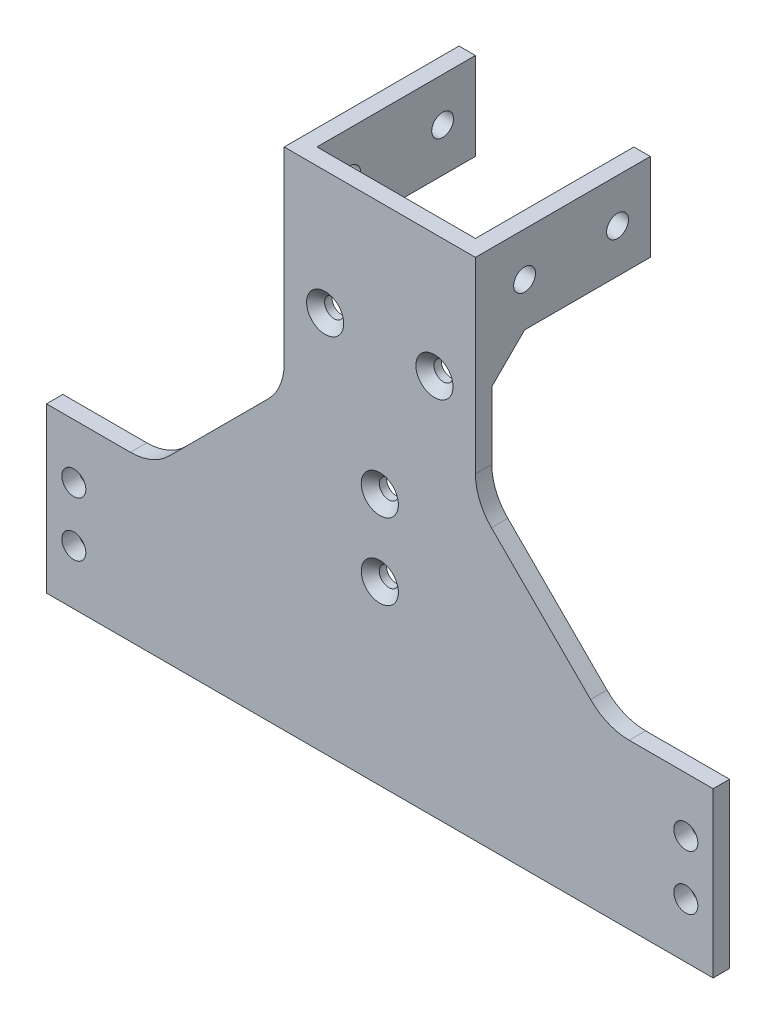
SolidWorks part; units mm, degrees
ref_plane "Front Plane" through (0, 0, 0) normal (0, 0, 1) x (1, 0, 0)
ref_plane "Top Plane" through (0, 0, 0) normal (0, 1, 0) x (1, 0, 0)
ref_plane "Right Plane" through (0, 0, 0) normal (1, 0, 0) x (0, 0, -1)
sketch "Sketch1" plane through (0, 0, 0) normal (0, 0, 1) x (1, 0, 0)
  line L0 (0, 15) -> (0, -15) construction
  line L1 (-61, -15) -> (61, -15)
  line L2 (-61, -15) -> (-61, 15)
  line L3 (-61, 15) -> (61, 15)
  line L4 (61, -15) -> (61, 15)
  line L5 (-61, -15) -> (61, 15) construction
  line L6 (-61, 15) -> (61, -15) construction
  line L7 (-61, 0) -> (61, 0) construction
  circle A0 centre (-56, 5) radius 2.2
  circle A1 centre (-56, -5) radius 2.2
  circle A2 centre (56, -5) radius 2.2
  circle A3 centre (56, 5) radius 2.2
  point P0 (0, 0)
  dimension "D5" = 4.4
  dimension "D1" = 122
  dimension "D2" = 5
  dimension "D3" = 10
  dimension "D4" = 5
extrude "Boss-Extrude1" add sketch "Sketch1" along normal blind 3
sketch "Sketch2" plane through (0, 0, 3) normal (0, 0, 1) x (1, 0, 0)
  line L0 (61, 15) -> (-61, 15) construction
  line L1 (-17.5, 15) -> (17.5, 15)
  line L2 (-17.5, 15) -> (-17.5, 77.46)
  line L3 (-17.5, 77.46) -> (17.5, 77.46)
  line L4 (17.5, 15) -> (17.5, 77.46)
  line L5 (0, 77.46) -> (0, 15) construction
  line L6 (-17.5, 57) -> (17.5, 57) construction
  circle A0 centre (0, 17.3) radius 1.75
  circle A1 centre (10, 54.9) radius 1.75
  circle A2 centre (0, 31.2) radius 1.75
  circle A3 centre (-10, 54.9) radius 1.75
  point P19 (10, 50.3993)
  dimension "D4" = 3.5
  dimension "D5" = 3.5
  dimension "D9" = 3.5
  dimension "D1" = 0
  dimension "D2" = 62.46
  dimension "D3" = 42
  dimension "D6" = 10
  dimension "D7" = 35
  dimension "D8" = 37.6
  dimension "D10" = 23.7
  dimension "D11" = 2.1
extrude "Boss-Extrude2" add sketch "Sketch2" against normal blind 3
sketch "Sketch3" plane through (0, 0, 3) normal (0, 0, 1) x (1, 0, 0)
  line L0 (-41.5, 15) -> (-17.5, 39)
  line L1 (-17.5, 15) -> (-61, 15) construction
  line L2 (-17.5, 77.46) -> (-17.5, 15) construction
  line L3 (-17.5, 39) -> (-17.5, 15)
  line L4 (-17.5, 15) -> (-41.5, 15)
  line L5 (0, 77.46) -> (0, 0) construction
  line L6 (17.5, 77.46) -> (-17.5, 77.46) construction
  line L7 (17.5, 39) -> (17.5, 15)
  line L8 (41.5, 15) -> (17.5, 39)
  line L9 (17.5, 15) -> (41.5, 15)
  dimension "D1" = 24
  dimension "D2" = 24
extrude "Boss-Extrude3" add sketch "Sketch3" against normal blind 3
fillet "Fillet1" radius 10 4 edges at (41.5, 15, 1.5) (17.5, 39, 1.5) (-41.5, 15, 1.5) (-17.5, 39, 1.5)
chamfer "Chamfer1" distance 1.65 angle 45 4 edges at (11.75, 54.9, 3) (-11.75, 54.9, 3) (1.75, 17.3, 3) (1.75, 31.2, 3)
sketch "Sketch4" plane through (17.5, 0, 0) normal (1, 0, 0) x (0, 0, -1)
  line L0 (14.5, 77.46) -> (14.5, 61.46) construction
  line L1 (-3, 77.46) -> (29, 77.46)
  line L2 (-3, 77.46) -> (-3, 61.46)
  line L3 (-3, 61.46) -> (29, 61.46)
  line L4 (29, 77.46) -> (29, 61.46)
  line L5 (29, 69.46) -> (-3, 69.46) construction
  circle A2 centre (23, 69.46) radius 2
  circle A3 centre (6, 69.46) radius 2
  dimension "D3" = 4
  dimension "D1" = 32
  dimension "D2" = 14.5
  dimension "D4" = 16
  dimension "D5" = 6
extrude "Boss-Extrude4" add sketch "Sketch4" against normal blind 3
mirror "Mirror1" about plane through (0, 0, 0) normal (1, 0, 0) of "Boss-Extrude4"
chamfer "Chamfer2" distance 6 angle 45 2 edges at (-16, 61.46, 0) (16, 61.46, 0)
